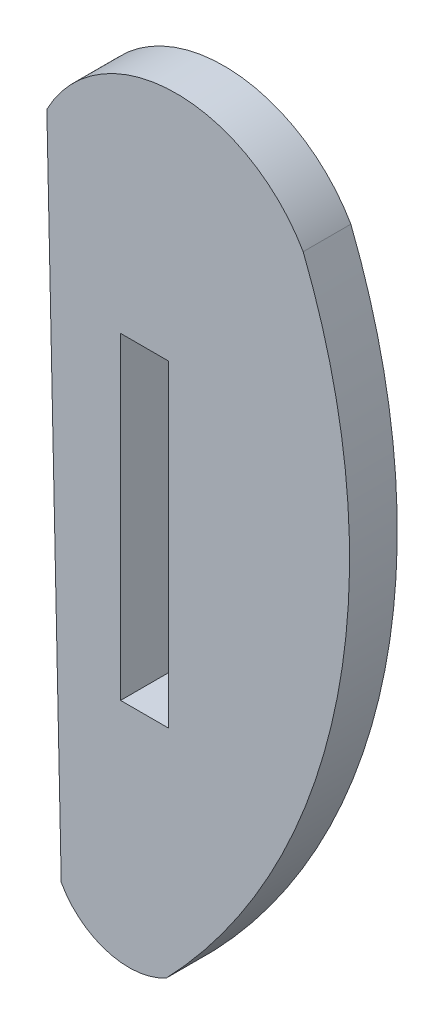
SolidWorks part; units mm, degrees
ref_plane "Front" through (0, 0, 0) normal (0, 0, 1) x (1, 0, 0)
ref_plane "Top" through (0, 0, 0) normal (0, 1, 0) x (1, 0, 0)
ref_plane "Right" through (0, 0, 0) normal (1, 0, 0) x (0, 0, -1)
sketch "Sketch1" plane through (0, 0, 0) normal (0, 0, 1) x (1, 0, 0)
  line L3 (-720.9285, -130.235) -> (-721.8344, -88.5619)
  line L16 (-717.1952, -118.4509) -> (-714.1952, -118.4509)
  line L17 (-714.1952, -118.4509) -> (-714.1952, -98.4509)
  line L18 (-714.1952, -98.4509) -> (-717.1952, -98.4509)
  line L19 (-717.1952, -98.4509) -> (-717.1952, -118.4509)
  arc A0 (-721.8344, -88.5619) -> (-705.7076, -88.257) centre (-713.6879, -92.8071) cw
  arc A1 (-705.7076, -88.257) -> (-714.3124, -132.1346) centre (-744.0949, -103.5115) cw
  arc A2 (-714.3124, -132.1346) -> (-720.9285, -130.235) centre (-716.6706, -127.8767) cw
  dimension "D1" = 3
  dimension "D2" = 20
extrude "Base-Extrude" add sketch "Sketch1" along normal blind 3
